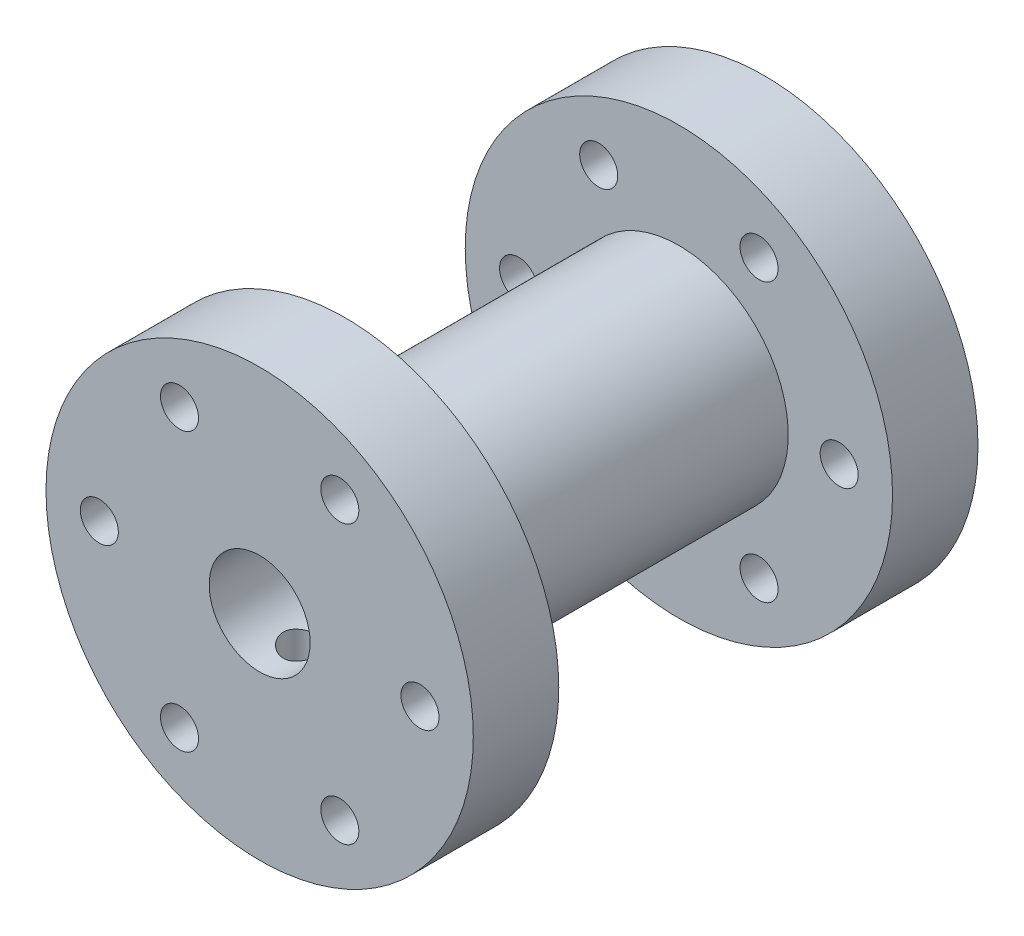
SolidWorks part; units mm, degrees
material "ABS"
ref_plane "Alzado" through (0, 0, 0) normal (0, 0, 1) x (1, 0, 0)
ref_plane "Planta" through (0, 0, 0) normal (0, 1, 0) x (1, 0, 0)
ref_plane "Vista lateral" through (0, 0, 0) normal (1, 0, 0) x (0, 0, -1)
sketch "Croquis2" plane through (0, 0, 0) normal (1, 0, 0) x (0, 0, -1)
  line L1 (-9.92, 6.5) -> (9.92, 6.5)
  line L2 (9.92, 6.5) -> (9.92, 12.7)
  line L3 (9.92, 12.7) -> (15, 12.7)
  line L4 (15, 12.7) -> (15, 0)
  line L5 (15, 0) -> (-15, 0)
  line L6 (-15, 12.7) -> (-15, 0)
  line L7 (-9.92, 12.7) -> (-15, 12.7)
  line L8 (-9.92, 6.5) -> (-9.92, 12.7)
  dimension "D1" = 6.5
  dimension "D2" = 12.7
  dimension "D3" = 5.08
  dimension "D4" = 30
revolve "Revolución1" add sketch "Croquis2" angle 360 about L5
sketch "Croquis3" plane through (0, 0, 15) normal (0, 0, 1) x (1, 0, 0)
  circle A0 centre (0, 0) radius 3
  dimension "D1" = 6
extrude "Cortar-Extruir1" cut sketch "Croquis3" against normal through all
hole_wizard "Taladro roscado #4-403" positions "Croquis8" profile "Croquis7" tap size "#4-40" standard "Ansi Inch"
sketch "Croquis8" plane through (0, 0, -9.92) normal (0, 0, 1) x (1, 0, 0)
  circle A0 centre (0, 0) radius 9.53 construction
  point P8 (-9.53, 0)
  point P16 (-4.765, 8.2532)
  point P17 (4.765, 8.2532)
  point P18 (9.53, 0)
  point P19 (4.765, -8.2532)
  point P20 (-4.765, -8.2532)
  point P21 (0, 0)
  dimension "D1" = 19.06
  dimension "D2" = 6
sketch "Croquis7" plane through (-9.53, 0, -9.92) normal (1, 0, 0) x (0, -1, 0)
  line L0 (0, 0) -> (0, 5.08)
  line L1 (0, 5.08) -> (1.1303, 5.08)
  line L2 (1.1303, 5.08) -> (1.1303, 0)
  line L5 (1.1303, 0) -> (0, 0)
  line L11 (0, -6.35) -> (0, 107.95) construction
  dimension "Diámetro de perforador para roscar hasta el siguiente" = 2.2606
  dimension "Profundidad de perforador para roscar hasta el siguiente" = 5.08
cosmetic thread "Rosca de taladro13" parameters "D2"=2.8448
cosmetic thread "Rosca de taladro14" parameters "D2"=2.8448
cosmetic thread "Rosca de taladro15" parameters "D2"=2.8448
cosmetic thread "Rosca de taladro16" parameters "D2"=2.8448
cosmetic thread "Rosca de taladro17" parameters "D2"=2.8448
cosmetic thread "Rosca de taladro18" parameters "D2"=2.8448
hole_wizard "Taladro roscado #4-405" positions "Croquis12" profile "Croquis11" tap size "#4-40" standard "Ansi Inch"
sketch "Croquis12" plane through (0, 0, 15) normal (0, 0, 1) x (1, 0, 0)
  circle A0 centre (0, 0) radius 9.53 construction
  point P5 (-9.53, 0)
  point P12 (-4.765, 8.2532)
  point P13 (4.765, 8.2532)
  point P14 (9.53, 0)
  point P15 (4.765, -8.2532)
  point P16 (-4.765, -8.2532)
  dimension "D1" = 19.06
  dimension "D2" = 6
sketch "Croquis11" plane through (-9.53, 0, 15) normal (1, 0, 0) x (0, -1, 0)
  line L0 (0, 0) -> (0, 9.5492)
  line L1 (0, 9.5492) -> (1.1303, 8.87)
  line L2 (1.1303, 8.87) -> (1.1303, 0)
  line L5 (1.1303, 0) -> (0, 0)
  line L10 (0, 9.5492) -> (-1.1303, 8.87) construction
  line L11 (0, -6.35) -> (0, 107.95) construction
  dimension "Diámetro de perforador para roscar" = 2.2606
  dimension "Profundidad de perforador para roscar" = 8.87
  dimension "Ángulo de perforador" = 118
cosmetic thread "Rosca de taladro21" parameters "D1"=5.08, "D2"=2.8448
cosmetic thread "Rosca de taladro22" parameters "D1"=5.08, "D2"=2.8448
cosmetic thread "Rosca de taladro23" parameters "D1"=5.08, "D2"=2.8448
cosmetic thread "Rosca de taladro24" parameters "D1"=5.08, "D2"=2.8448
cosmetic thread "Rosca de taladro25" parameters "D1"=5.08, "D2"=2.8448
cosmetic thread "Rosca de taladro26" parameters "D1"=5.08, "D2"=2.8448
ref_plane "Plano1" through (0, -12.7, 0) normal (0, -1, 0) x (-1, 0, 0)
hole_wizard "Taladro roscado #4-404" positions "Croquis10" profile "Croquis9" tap size "#4-40" standard "Ansi Inch"
sketch "Croquis10" plane through (0, -12.7, 0) normal (0, -1, 0) x (-1, 0, 0)
  line L7 (12.7, 15) -> (-12.7, 15) construction
  line L8 (-12.7, 9.92) -> (12.7, 9.92) construction
  line L9 (6.5, 0) -> (-6.5, 0) construction
  line L10 (6.5, -9.92) -> (6.5, 9.92) construction
  line L11 (-6.5, 9.92) -> (-6.5, -9.92) construction
  point P0 (0, 12.46)
  point P2 (0, 6.92)
  point P38 (0, -6.92)
  point P39 (0, -12.46)
  dimension "D1" = 2.54
  dimension "D2" = 3
sketch "Croquis9" plane through (0, -12.7, -12.46) normal (1, 0, 0) x (0, 0, -1)
  line L0 (0, 0) -> (0, 13.3782)
  line L1 (0, 13.3782) -> (1.1303, 12.699)
  line L2 (1.1303, 12.699) -> (1.1303, 0)
  line L5 (1.1303, 0) -> (0, 0)
  line L10 (0, 13.3782) -> (-1.1303, 12.699) construction
  line L11 (0, -6.35) -> (0, 107.95) construction
  dimension "Diámetro de perforador para roscar" = 2.2606
  dimension "Profundidad de perforador para roscar" = 12.699
  dimension "Ángulo de perforador" = 118
cosmetic thread "Rosca de taladro29" parameters "D1"=5.69, "D2"=2.8448
cosmetic thread "Rosca de taladro30" parameters "D1"=5.69, "D2"=2.8448
cosmetic thread "Rosca de taladro31" parameters "D1"=5.69, "D2"=2.8448
cosmetic thread "Rosca de taladro32" parameters "D1"=5.69, "D2"=2.8448
